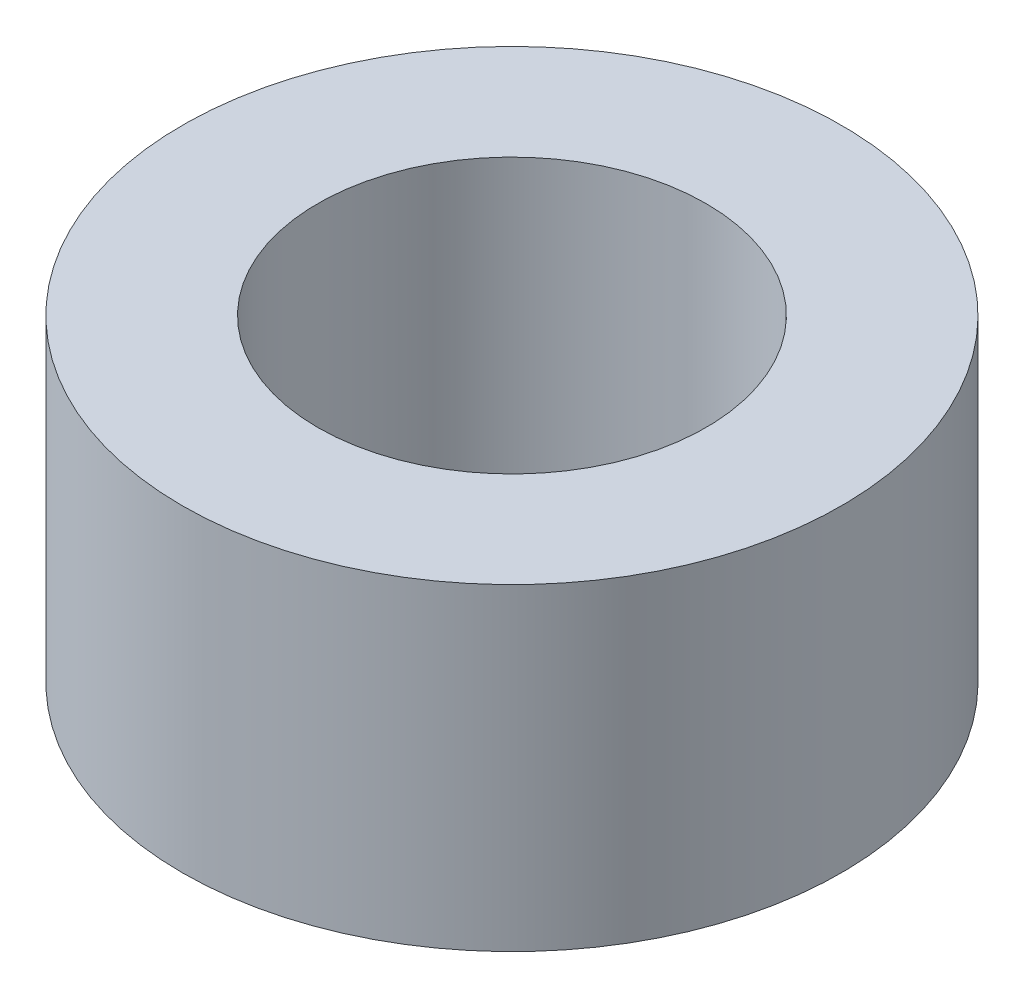
SolidWorks part; units mm, degrees
material "PLA/ABS"
ref_plane "Front Plane" through (0, 0, 0) normal (0, 0, 1) x (1, 0, 0)
ref_plane "Top Plane" through (0, 0, 0) normal (0, 1, 0) x (1, 0, 0)
ref_plane "Right Plane" through (0, 0, 0) normal (1, 0, 0) x (0, 0, -1)
other "Bounding Box"
ref_plane "Default Plane" through (-8.9266, -12.7485, 0) normal (-0.1736, 0.9848, 0) x (0.9848, 0.1736, 0)
sketch "Sketch1" plane through (0, 0, 0) normal (0, 1, 0) x (1, 0, 0)
  circle A0 centre (0, 0) radius 3.3655
  circle A1 centre (0, 0) radius 5.715
  dimension "D1" = 6.731
  dimension "D2" = 11.43
extrude "Boss-Extrude1" add sketch "Sketch1" along normal blind 5.5118
